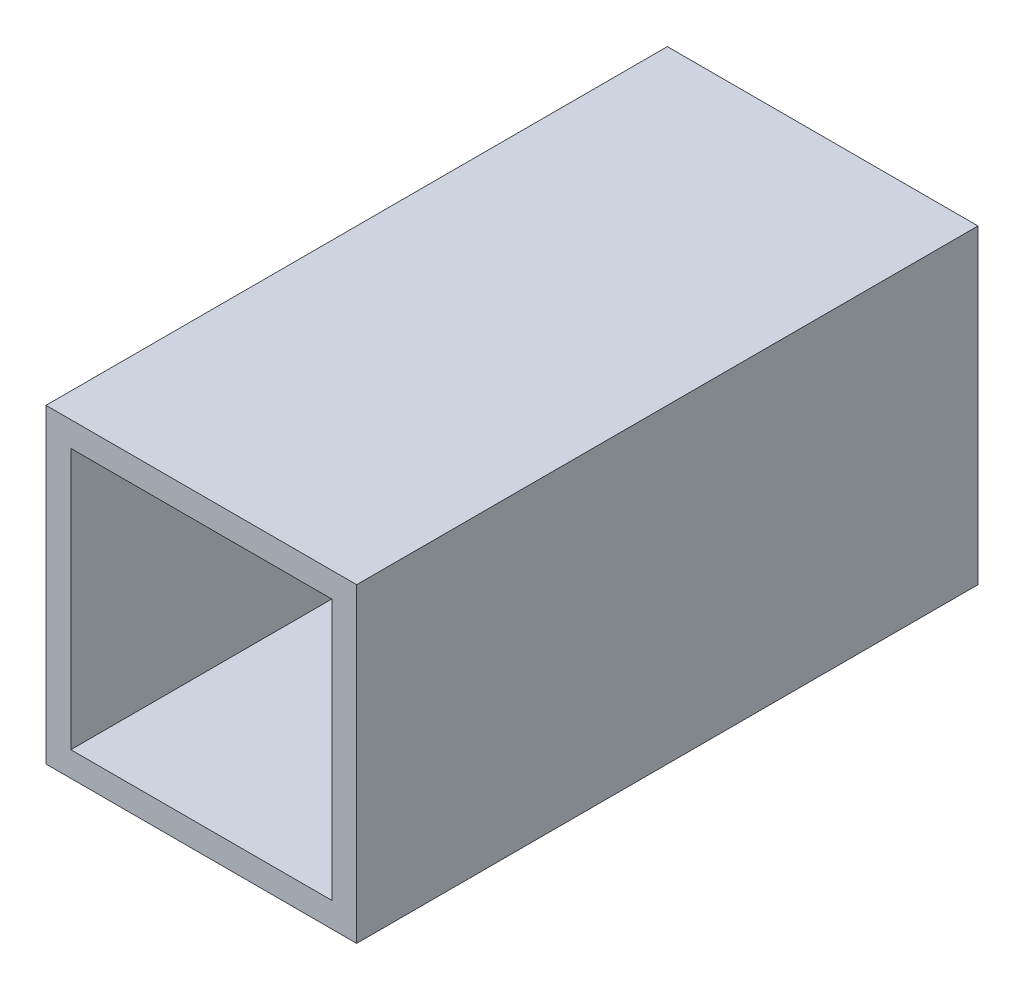
SolidWorks part; units mm, degrees
ref_plane "Front Plane" through (0, 0, 0) normal (0, 0, 1) x (1, 0, 0)
ref_plane "Top Plane" through (0, 0, 0) normal (0, 1, 0) x (1, 0, 0)
ref_plane "Right Plane" through (0, 0, 0) normal (1, 0, 0) x (0, 0, -1)
sketch "Sketch1" plane through (0, 0, 0) normal (0, 0, 1) x (1, 0, 0)
  line L1 (-67.519, -45.2538) -> (-42.119, -45.2538)
  line L2 (-67.519, -45.2538) -> (-67.519, -19.8538)
  line L3 (-67.519, -19.8538) -> (-42.119, -19.8538)
  line L4 (-42.119, -45.2538) -> (-42.119, -19.8538)
  line L5 (-67.519, -45.2538) -> (-42.119, -19.8538) construction
  line L6 (-67.519, -19.8538) -> (-42.119, -45.2538) construction
  point P0 (-54.819, -32.5538)
  dimension "D1" = 25.4
  dimension "D2" = 25.4
extrude "Boss-Extrude1" add sketch "Sketch1" along normal blind 50.8
sketch "Sketch2" plane through (0, 0, 50.8) normal (0, 0, 1) x (1, 0, 0)
  line L0 (-67.519, -19.8538) -> (-67.519, -45.2538) construction
  line L1 (-65.487, -21.8858) -> (-44.151, -21.8858)
  line L2 (-65.487, -21.8858) -> (-65.487, -43.2218)
  line L3 (-65.487, -43.2218) -> (-44.151, -43.2218)
  line L4 (-44.151, -21.8858) -> (-44.151, -43.2218)
  line L5 (-65.487, -21.8858) -> (-44.151, -43.2218) construction
  line L6 (-65.487, -43.2218) -> (-44.151, -21.8858) construction
  line L7 (-42.119, -19.8538) -> (-67.519, -19.8538) construction
  line L8 (-42.119, -45.2538) -> (-42.119, -19.8538) construction
  line L9 (-67.519, -45.2538) -> (-42.119, -45.2538) construction
  point P0 (-54.819, -32.5538)
  dimension "D1" = 2.032
  dimension "D2" = 2.032
  dimension "D3" = 2.032
  dimension "D4" = 2.032
extrude "Cut-Extrude1" cut sketch "Sketch2" against normal through all
